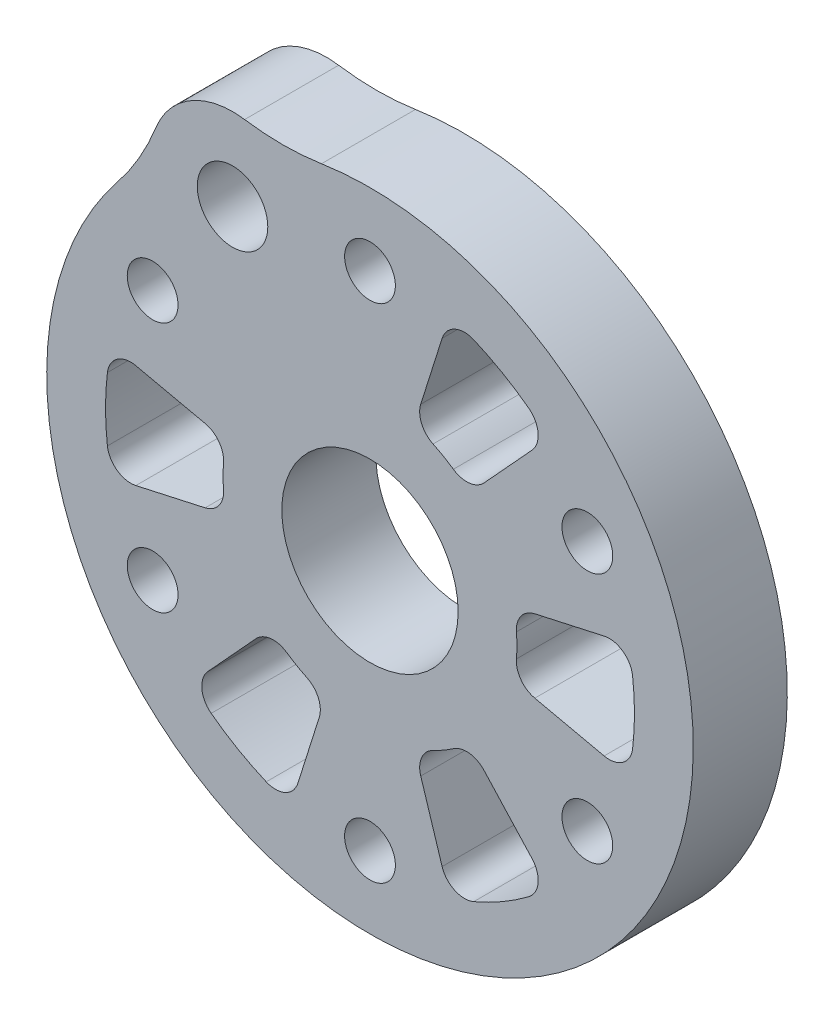
SolidWorks part; units mm, degrees
ref_plane "Plan de face" through (0, 0, 0) normal (0, 0, 1) x (1, 0, 0)
ref_plane "Plan de dessus" through (0, 0, 0) normal (0, 1, 0) x (1, 0, 0)
ref_plane "Plan de droite" through (0, 0, 0) normal (1, 0, 0) x (0, 0, -1)
sketch "Esquisse1" plane through (0, 0, 0) normal (0, 0, 1) x (1, 0, 0)
  line L0 (-4.0606, 13.1367) -> (0, 0) construction
  line L1 (0, 0) -> (-9.3464, 10.085) construction
  line L3 (0, 0) -> (-9.8486, 0) construction
  line L4 (-5.8467, 10.1268) -> (0, 0) construction
  arc A0 (-9.3464, 10.085) -> (-4.0606, 13.1367) centre (0, 0) ccw
  circle A2 centre (0, 0) radius 3.75
  arc A3 (-9.3464, 10.085) -> (-4.0606, 13.1367) centre (-5.8467, 10.1268) cw
  circle A4 centre (-5.8467, 10.1268) radius 1.5
  dimension "D1" = 27.5
  dimension "D2" = 7.5
  dimension "D4" = 3
  dimension "D5" = 3.5
  dimension "D3" = 60
extrude "Boss.-Extru.1" add sketch "Esquisse1" along normal blind 4
sketch "Esquisse2" plane through (0, 0, 4) normal (0, 0, 1) x (1, 0, 0)
  line L0 (0, 10.675) -> (0, 0) construction
  line L1 (0, 0) -> (0, -10.675) construction
  circle A0 centre (0, 10.675) radius 1.08
  dimension "D2" = 2.16
  dimension "D1" = 21.35
extrude "Enlèv. mat.-Extru.1" cut sketch "Esquisse2" against normal up to next
pattern_circular "Répétition circulaire1" count 6 over 360 about axis through (0, 0, 0) along (0, 0, 1) of "Enlèv. mat.-Extru.1"
fillet "Congé1" radius 11 2 edges at (-4.0606, 13.1367, 2) (-9.3464, 10.085, 2)
sketch "Esquisse3" plane through (0, 0, 0) normal (0, 0, -1) x (-1, 0, 0)
  line L0 (0, 0) -> (-8.7439, 0) construction
  line L1 (0, 0) -> (-4.6241, 8.0091) construction
  line L3 (-3.3829, 10.7293) -> (-1.8794, 5.9607)
  line L5 (-4.2224, 4.608) -> (-7.6004, 8.2944)
  line L6 (-4.2224, 4.608) -> (-2.5335, 2.7648) construction
  line L7 (-7.6004, 8.2944) -> (-9.2894, 10.1376) construction
  line L8 (-1.8794, 5.9607) -> (0, 0) construction
  arc A0 (-4.2224, 4.608) -> (-1.8794, 5.9607) centre (0, 0) cw
  arc A1 (-7.6004, 8.2944) -> (-3.3829, 10.7293) centre (0, 0) cw
  circle A2 centre (0, 0) radius 3.75 construction
  arc A3 (2.0646, 13.5941) -> (10.7405, 8.5851) centre (0, 0) ccw construction
  dimension "D1" = 60
  dimension "D2" = 5
  dimension "D3" = 25
extrude "Enlèv. mat.-Extru.2" cut sketch "Esquisse3" against normal up to next
fillet "Congé2" radius 1 4 edges at (3.3829, 10.7293, 2) (1.8794, 5.9607, 2) (4.2224, 4.608, 2) (7.6004, 8.2944, 2)
pattern_circular "Répétition circulaire2" count 5 every 60 about axis through (0, 0, 0) along (0, 0, 1) of "Enlèv. mat.-Extru.2", "Congé2"
